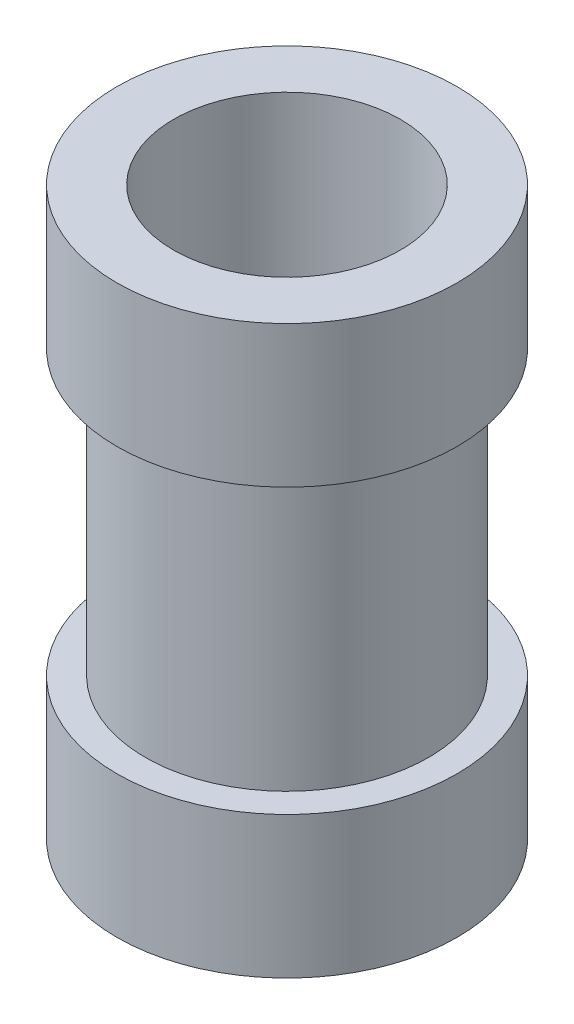
SolidWorks part; units mm, degrees
ref_plane "Front Plane" through (0, 0, 0) normal (0, 0, 1) x (1, 0, 0)
ref_plane "Top Plane" through (0, 0, 0) normal (0, 1, 0) x (1, 0, 0)
ref_plane "Right Plane" through (0, 0, 0) normal (1, 0, 0) x (0, 0, -1)
sketch "Sketch1" plane through (0, 0, 0) normal (0, 0, 1) x (1, 0, 0)
  line L0 (0, 0) -> (0, 5)
  line L1 (0, 5) -> (-3, 5)
  line L2 (-3, 5) -> (-3, 2.5)
  line L3 (-3, 2.5) -> (-2.5, 2.5)
  line L4 (-2.5, 2.5) -> (-2.5, 0)
  line L5 (-2.5, 0) -> (0, 0)
  dimension "D1" = 5
  dimension "D2" = 2.5
  dimension "D3" = 3
  dimension "D4" = 2.5
revolve "Revolve1" add sketch "Sketch1" angle 360 about L0
mirror "Mirror1" about plane through (-2.5, 0, 0) normal (0, 1, 0) of "Revolve1"
sketch "Sketch2" plane through (0, 5, 0) normal (0, 1, 0) x (1, 0, 0)
  circle A0 centre (0, 0) radius 2
  dimension "D1" = 4
extrude "Cut-Extrude1" cut sketch "Sketch2" against normal through all
